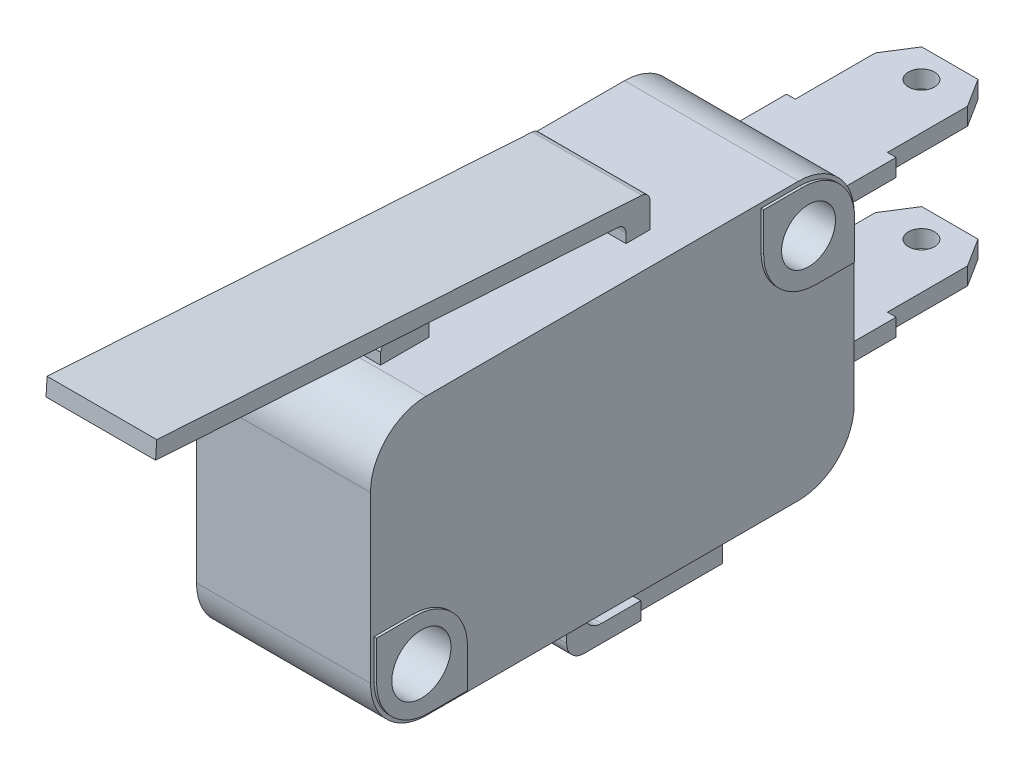
SolidWorks part; units mm, degrees
ref_plane "Front" through (0, 0, 0) normal (0, 0, 1) x (1, 0, 0)
ref_plane "Top" through (0, 0, 0) normal (0, 1, 0) x (1, 0, 0)
ref_plane "Right" through (0, 0, 0) normal (1, 0, 0) x (0, 0, -1)
ref_plane "Plane1" through (3.15, 0, 0) normal (1, 0, 0) x (0, 0, -1)
sketch "Sketch1" plane through (3.15, 0, 0) normal (1, 0, 0) x (0, 0, -1)
  line L0 (2.633, 8.9557) -> (4.0137, 8.9557)
  line L1 (4.0137, 8.9557) -> (4.0137, 9.8696)
  line L2 (4.0137, 9.8696) -> (2.6967, 9.9537)
  line L3 (2.6967, 9.9537) -> (2.633, 8.9557)
extrude "Boss-Extrude1" add sketch "Sketch1" against normal blind 6.3
sketch "Sketch2" plane through (0, 8.9557, 0) normal (0, -1, 0) x (1, 0, 0)
  line L0 (3.15, -2.633) -> (3.15, -4.0137)
  line L1 (3.15, -4.0137) -> (-3.15, -4.0137)
  line L2 (-3.15, -4.0137) -> (-3.15, -2.633)
  line L3 (-3.15, -2.633) -> (3.15, -2.633)
extrude "Boss-Extrude2" add sketch "Sketch2" along normal blind 16.9057
sketch "Sketch3" plane through (3.15, 0, 0) normal (1, 0, 0) x (0, 0, -1)
  line L0 (4.0137, 9.8696) -> (4.0137, -7.95)
  line L1 (4.0137, -7.95) -> (2.633, -7.95)
  line L2 (2.633, -7.95) -> (2.633, 9.8696)
  line L3 (2.633, 9.8696) -> (4.0137, 9.8696)
extrude "Boss-Extrude3" add sketch "Sketch3" along normal blind 1.85
sketch "Sketch4" plane through (0, -0.1311, -2.0529) normal (0, 0.0637, 0.998) x (1, 0, 0)
  line L0 (3.15, 9.1053) -> (-3.15, 9.1053)
  line L1 (-3.15, 9.1053) -> (-3.15, 10.1053)
  line L2 (-3.15, 10.1053) -> (3.15, 10.1053)
  line L3 (3.15, 10.1053) -> (3.15, 9.1053)
extrude "Boss-Extrude4" add sketch "Sketch4" along normal blind 27.0891
sketch "Sketch5" plane through (0, 0, -4.0137) normal (0, 0, -1) x (-1, 0, 0)
  line L0 (3.15, -7.95) -> (-5, -7.95)
  line L1 (-5, -7.95) -> (-5, 9.8696)
  line L2 (-5, 9.8696) -> (3.15, 9.8696)
  line L3 (3.15, 9.8696) -> (3.15, -7.95)
extrude "Boss-Extrude5" add sketch "Sketch5" along normal blind 9.8863
sketch "Sketch6" plane through (0, 9.8696, 0) normal (0, 1, 0) x (-1, 0, 0)
  line L0 (-3.15, -4.0137) -> (-3.15, -2.633)
  line L1 (-3.15, -2.633) -> (-5, -2.633)
  line L2 (-5, -2.633) -> (-5, -13.9)
  line L3 (-5, -13.9) -> (3.15, -13.9)
  line L4 (3.15, -13.9) -> (3.15, -4.0137)
  line L5 (3.15, -4.0137) -> (-3.15, -4.0137)
extrude "Cut-Extrude1" cut sketch "Sketch6" against normal blind 0.9139
sketch "Sketch7" plane through (0, 8.9557, 0) normal (0, 1, 0) x (-1, 0, 0)
  line L0 (-3.15, -4.0137) -> (-3.15, -2.633)
  line L1 (-3.15, -2.633) -> (-5, -2.633)
  line L2 (-5, -2.633) -> (-5, -13.9)
  line L3 (-5, -13.9) -> (3.15, -13.9)
  line L4 (3.15, -13.9) -> (3.15, -4.0137)
  line L5 (3.15, -4.0137) -> (-3.15, -4.0137)
extrude "Cut-Extrude2" cut sketch "Sketch7" against normal blind 1.0057
sketch "Sketch8" plane through (0, 0, -2.633) normal (0, 0, 1) x (1, 0, 0)
  line L0 (-3.15, 7.95) -> (5, 7.95)
  line L1 (5, 7.95) -> (5, -7.95)
  line L2 (5, -7.95) -> (-3.15, -7.95)
  line L3 (-3.15, -7.95) -> (-3.15, 7.95)
extrude "Boss-Extrude6" add sketch "Sketch8" along normal blind 16.533
sketch "Sketch9" plane through (-3.15, 0, 0) normal (-1, 0, 0) x (0, 0, 1)
  line L0 (13.9, 7.95) -> (13.9, -7.95)
  line L1 (13.9, -7.95) -> (-13.9, -7.95)
  line L2 (-13.9, -7.95) -> (-13.9, 7.95)
  line L3 (-13.9, 7.95) -> (13.9, 7.95)
extrude "Boss-Extrude7" add sketch "Sketch9" along normal blind 1.85
sketch "Sketch10" plane through (0, -7.95, 0) normal (0, -1, 0) x (1, 0, 0)
  line L0 (-3.15, 0.775) -> (3.15, 0.775)
  line L1 (3.15, 0.775) -> (3.15, -0.225)
  line L2 (3.15, -0.225) -> (-3.15, -0.225)
  line L3 (-3.15, -0.225) -> (-3.15, 0.775)
extrude "Boss-Extrude8" add sketch "Sketch10" along normal blind 3.3
sketch "Sketch11" plane through (0, 0, -0.225) normal (0, 0, -1) x (-1, 0, 0)
  line L0 (-3.15, -10.25) -> (3.15, -10.25)
  line L1 (3.15, -10.25) -> (3.15, -11.25)
  line L2 (3.15, -11.25) -> (-3.15, -11.25)
  line L3 (-3.15, -11.25) -> (-3.15, -10.25)
extrude "Boss-Extrude9" add sketch "Sketch11" along normal blind 9.5
sketch "Sketch12" plane through (0, -10.25, 0) normal (0, 1, 0) x (-1, 0, 0)
  line L0 (3.15, -3.4862) -> (2.65, -3.4862)
  line L1 (2.65, -3.4862) -> (2.65, -9.725)
  line L2 (2.65, -9.725) -> (3.15, -9.725)
  line L3 (3.15, -9.725) -> (3.15, -3.4862)
extrude "Cut-Extrude3" cut sketch "Sketch12" against normal through all
sketch "Sketch13" plane through (0, -10.25, 0) normal (0, 1, 0) x (-1, 0, 0)
  line L0 (-2.65, -9.725) -> (-2.65, -3.4862)
  line L1 (-2.65, -3.4862) -> (-3.15, -3.4862)
  line L2 (-3.15, -3.4862) -> (-3.15, -9.725)
  line L3 (-3.15, -9.725) -> (-2.65, -9.725)
extrude "Cut-Extrude4" cut sketch "Sketch13" against normal through all
sketch "Sketch14" plane through (0, 0, -13.9) normal (0, 0, -1) x (-1, 0, 0)
  line L0 (3.15, 4.475) -> (3.15, 3.475)
  line L1 (3.15, 3.475) -> (-3.15, 3.475)
  line L2 (-3.15, 3.475) -> (-3.15, 4.475)
  line L3 (-3.15, 4.475) -> (3.15, 4.475)
extrude "Boss-Extrude10" add sketch "Sketch14" along normal blind 10.5
sketch "Sketch15" plane through (0, 3.475, 0) normal (0, -1, 0) x (1, 0, 0)
  line L0 (3.15, -18.1612) -> (2.65, -18.1612)
  line L1 (2.65, -18.1612) -> (2.65, -24.4)
  line L2 (2.65, -24.4) -> (3.15, -24.4)
  line L3 (3.15, -24.4) -> (3.15, -18.1612)
extrude "Cut-Extrude5" cut sketch "Sketch15" against normal through all
sketch "Sketch16" plane through (0, 3.475, 0) normal (0, -1, 0) x (1, 0, 0)
  line L0 (-3.15, -24.4) -> (-2.65, -24.4)
  line L1 (-2.65, -24.4) -> (-2.65, -18.1612)
  line L2 (-2.65, -18.1612) -> (-3.15, -18.1612)
  line L3 (-3.15, -18.1612) -> (-3.15, -24.4)
extrude "Cut-Extrude6" cut sketch "Sketch16" against normal through all
sketch "Sketch17" plane through (0, 0, -13.9) normal (0, 0, -1) x (-1, 0, 0)
  line L0 (3.15, -3.475) -> (3.15, -4.475)
  line L1 (3.15, -4.475) -> (-3.15, -4.475)
  line L2 (-3.15, -4.475) -> (-3.15, -3.475)
  line L3 (-3.15, -3.475) -> (3.15, -3.475)
extrude "Boss-Extrude11" add sketch "Sketch17" along normal blind 10.5
sketch "Sketch18" plane through (0, -4.475, 0) normal (0, -1, 0) x (1, 0, 0)
  line L0 (3.15, -18.1612) -> (2.65, -18.1612)
  line L1 (2.65, -18.1612) -> (2.65, -24.4)
  line L2 (2.65, -24.4) -> (3.15, -24.4)
  line L3 (3.15, -24.4) -> (3.15, -18.1612)
extrude "Cut-Extrude7" cut sketch "Sketch18" against normal through all
sketch "Sketch19" plane through (0, -4.475, 0) normal (0, -1, 0) x (1, 0, 0)
  line L0 (-3.15, -24.4) -> (-2.65, -24.4)
  line L1 (-2.65, -24.4) -> (-2.65, -18.1612)
  line L2 (-2.65, -18.1612) -> (-3.15, -18.1612)
  line L3 (-3.15, -18.1612) -> (-3.15, -24.4)
extrude "Cut-Extrude8" cut sketch "Sketch19" against normal through all
sketch "Sketch20" plane through (5, 0, 0) normal (1, 0, 0) x (0, 0, -1)
  line L0 (8.55, 2.45) -> (8.55, 7.675)
  line L1 (8.55, 7.675) -> (13.775, 7.675)
  line L2 (13.775, 7.675) -> (13.775, 2.45)
  line L3 (13.775, 2.45) -> (8.55, 2.45)
extrude "Boss-Extrude12" add sketch "Sketch20" along normal blind 0.15
sketch "Sketch21" plane through (5, 0, 0) normal (1, 0, 0) x (0, 0, -1)
  line L0 (-13.7, -7.75) -> (-13.7, -2.525)
  line L1 (-13.7, -2.525) -> (-8.475, -2.525)
  line L2 (-8.475, -2.525) -> (-8.475, -7.75)
  line L3 (-8.475, -7.75) -> (-13.7, -7.75)
extrude "Boss-Extrude13" add sketch "Sketch21" along normal blind 0.15
ref_plane "Plane2" through (-2.15, 0, 0) normal (-1, 0, 0) x (0, -1, 0)
sketch "Sketch22" plane through (-2.15, 0, 0) normal (-1, 0, 0) x (0, -1, 0)
  line L0 (-8.6, 7.675) -> (-7.95, 7.675)
  line L1 (-7.95, 7.675) -> (-7.95, 10.475)
  line L2 (-7.95, 10.475) -> (-8.6, 10.475)
  arc A0 (-8.6, 10.475) -> (-8.6, 7.675) centre (-8.12, 9.075) ccw
extrude "Boss-Extrude14" add sketch "Sketch22" against normal blind 4.3
sketch "Sketch23" plane through (-5, 0, 0) normal (-1, 0, 0) x (0, 0, 1)
  line L0 (-8.55, 2.45) -> (-13.775, 2.45)
  line L1 (-13.775, 2.45) -> (-13.775, 7.675)
  line L2 (-13.775, 7.675) -> (-8.55, 7.675)
  line L3 (-8.55, 7.675) -> (-8.55, 2.45)
extrude "Boss-Extrude15" add sketch "Sketch23" along normal blind 0.15
sketch "Sketch24" plane through (-5, 0, 0) normal (-1, 0, 0) x (0, 0, 1)
  line L0 (13.7, -7.75) -> (8.475, -7.75)
  line L1 (8.475, -7.75) -> (8.475, -2.525)
  line L2 (8.475, -2.525) -> (13.7, -2.525)
  line L3 (13.7, -2.525) -> (13.7, -7.75)
extrude "Boss-Extrude16" add sketch "Sketch24" along normal blind 0.15
hole_wizard "#4 Clearance Hole1" positions "Sketch26" profile "Sketch25" hole size "#4" standard "ANSI Inch"
sketch "Sketch26" plane through (5.15, 0, 0) normal (1, 0, 0) x (0, 0, -1)
  point P0 (-11.125, -5.1)
sketch "Sketch25" plane through (5.15, -5.1, 11.125) normal (0, 1, 0) x (0, 0, -1)
  line L0 (0, 0) -> (0, 10.3)
  line L1 (0, 10.3) -> (1.7, 10.3)
  line L2 (1.7, 10.3) -> (1.7, 0)
  line L5 (1.7, 0) -> (0, 0)
  line L11 (0, -6.35) -> (0, 107.95) construction
  dimension "Thru Hole Dia." = 3.4
  dimension "Thru Hole Depth" = 10.3
hole_wizard "#00 Clearance Hole1" positions "Sketch28" profile "Sketch27" hole size "#00" standard "ANSI Inch"
sketch "Sketch28" plane through (0, -4.475, 0) normal (0, -1, 0) x (-1, 0, 0)
  point P0 (0, 22.7671)
sketch "Sketch27" plane through (0, -4.475, -22.7671) normal (1, 0, 0) x (0, 0, -1)
  line L0 (0, 0) -> (0, 1)
  line L1 (0, 1) -> (0.75, 1)
  line L2 (0.75, 1) -> (0.75, 0)
  line L5 (0.75, 0) -> (0, 0)
  line L11 (0, -6.35) -> (0, 107.95) construction
  dimension "Thru Hole Dia." = 1.5
  dimension "Thru Hole Depth" = 1
hole_wizard "#00 Clearance Hole2" positions "Sketch30" profile "Sketch29" hole size "#00" standard "ANSI Inch"
sketch "Sketch30" plane through (0, 4.475, 0) normal (0, 1, 0) x (1, 0, 0)
  point P0 (0, 22.7671)
sketch "Sketch29" plane through (0, 4.475, -22.7671) normal (1, 0, 0) x (0, 0, 1)
  line L0 (0, 0) -> (0, 15.725)
  line L1 (0, 15.725) -> (0.75, 15.725)
  line L2 (0.75, 15.725) -> (0.75, 0)
  line L5 (0.75, 0) -> (0, 0)
  line L11 (0, -6.35) -> (0, 107.95) construction
  dimension "Thru Hole Dia." = 1.5
  dimension "Thru Hole Depth" = 15.725
hole_wizard "#4 Clearance Hole2" positions "Sketch32" profile "Sketch31" hole size "#4" standard "ANSI Inch"
sketch "Sketch32" plane through (5.15, 0, 0) normal (1, 0, 0) x (0, 0, -1)
  point P0 (11.125, 5.1)
sketch "Sketch31" plane through (5.15, 5.1, -11.125) normal (0, 1, 0) x (0, 0, -1)
  line L0 (0, 0) -> (0, 10.3)
  line L1 (0, 10.3) -> (1.55, 10.3)
  line L2 (1.55, 10.3) -> (1.55, 0)
  line L5 (1.55, 0) -> (0, 0)
  line L11 (0, -6.35) -> (0, 107.95) construction
  dimension "Thru Hole Dia." = 3.1
  dimension "Thru Hole Depth" = 10.3
hole_wizard "#00 Clearance Hole3" positions "Sketch34" profile "Sketch33" hole size "#00" standard "ANSI Inch"
sketch "Sketch34" plane through (0, -10.25, 0) normal (0, 1, 0) x (1, 0, 0)
  point P0 (0, 8.0921)
sketch "Sketch33" plane through (0, -10.25, -8.0921) normal (1, 0, 0) x (0, 0, 1)
  line L0 (0, 0) -> (0, 1)
  line L1 (0, 1) -> (0.75, 1)
  line L2 (0.75, 1) -> (0.75, 0)
  line L5 (0.75, 0) -> (0, 0)
  line L11 (0, -6.35) -> (0, 107.95) construction
  dimension "Thru Hole Dia." = 1.5
  dimension "Thru Hole Depth" = 1
chamfer "Chamfer1" distance 1.6329 angle 32.32 2 edges at (-2.65, -3.975, -24.4) (-2.65, 3.975, -24.4)
chamfer "Chamfer2" distance 1.033 angle 57.68 2 edges at (2.65, 3.975, -24.4) (2.65, -3.975, -24.4)
chamfer "Chamfer3" distance 1.6329 angle 32.32 2 edges at (2.65, -10.75, -9.725) (-2.65, -10.75, -9.725)
fillet "Fillet1" radius 0.5 2 edges at (0, 8.9557, -2.633)
fillet "Fillet2" radius 1 2 edges at (0, -10.25, -0.225) (0, -11.25, 0.775)
fillet "Fillet3" radius 3 8 edges at (5.075, 7.675, -13.775) (5.075, -7.75, 13.7) (-5.075, -2.525, 8.475) (5.075, 2.45, -8.55) (-5.075, -7.75, 13.7) (-5.075, 2.45, -8.55) (-5.075, 7.675, -13.775) (5.075, -2.525, 8.475)
fillet "Fillet4" radius 3.2 4 edges at (0, -7.95, -13.9) (0, -7.95, 13.9) (0, 7.95, -13.9) (0, 7.95, 13.9)
